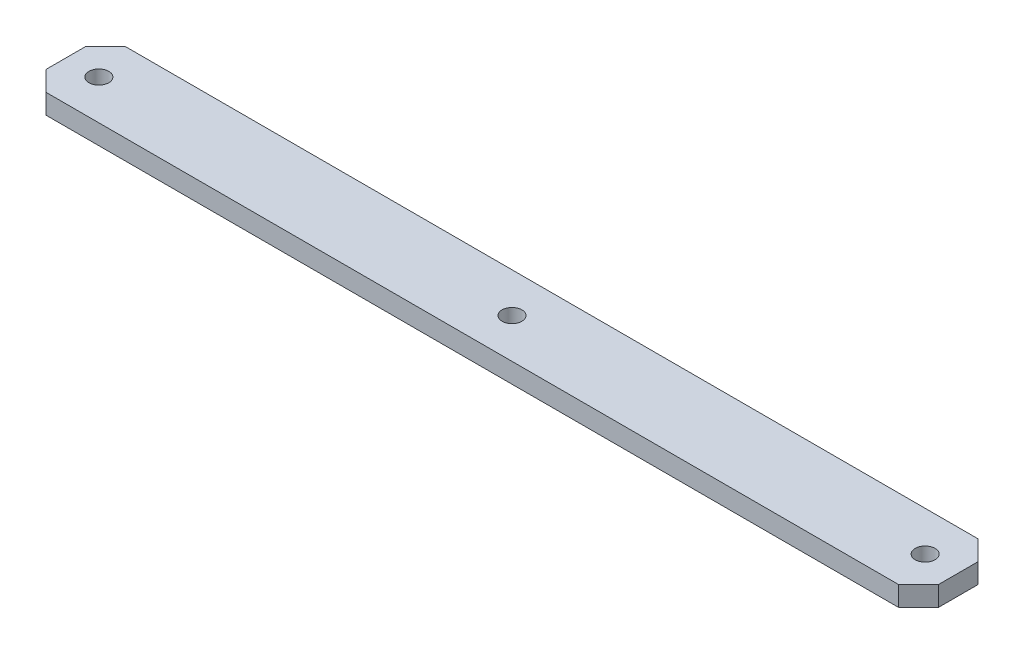
SolidWorks part; units mm, degrees
ref_plane "Front Plane" through (0, 0, 0) normal (0, 0, 1) x (1, 0, 0)
ref_plane "Top Plane" through (0, 0, 0) normal (0, 1, 0) x (1, 0, 0)
ref_plane "Right Plane" through (0, 0, 0) normal (1, 0, 0) x (0, 0, -1)
sketch "Sketch1" plane through (0, 0, 0) normal (0, 1, 0) x (1, 0, 0)
  line L0 (-67.5, 3) -> (-64.5, 6)
  line L1 (-64.5, 6) -> (64.5, 6)
  line L2 (-67.5, 3) -> (-67.5, -3)
  line L3 (-64.5, -6) -> (64.5, -6)
  line L4 (67.5, 3) -> (67.5, -3)
  line L5 (-67.5, 6) -> (67.5, -6) construction
  line L6 (-67.5, -6) -> (67.5, 6) construction
  line L7 (-67.5, -3) -> (-64.5, -6)
  line L8 (64.5, 6) -> (67.5, 3)
  line L9 (64.5, -6) -> (67.5, -3)
  circle A0 centre (-62.5, 0) radius 1.5
  circle A1 centre (0, 0) radius 1.5
  circle A2 centre (62.5, 0) radius 1.5
  point P0 (0, 0)
  dimension "D3" = 3
  dimension "D1" = 135
  dimension "D2" = 12
  dimension "D4" = 62.5
  dimension "D5" = 62.5
extrude "Boss-Extrude1" add sketch "Sketch1" along normal blind 3 contours A0 | L8 L4 L9 L3 L7 L2 L0 L1 | A1 | A2
